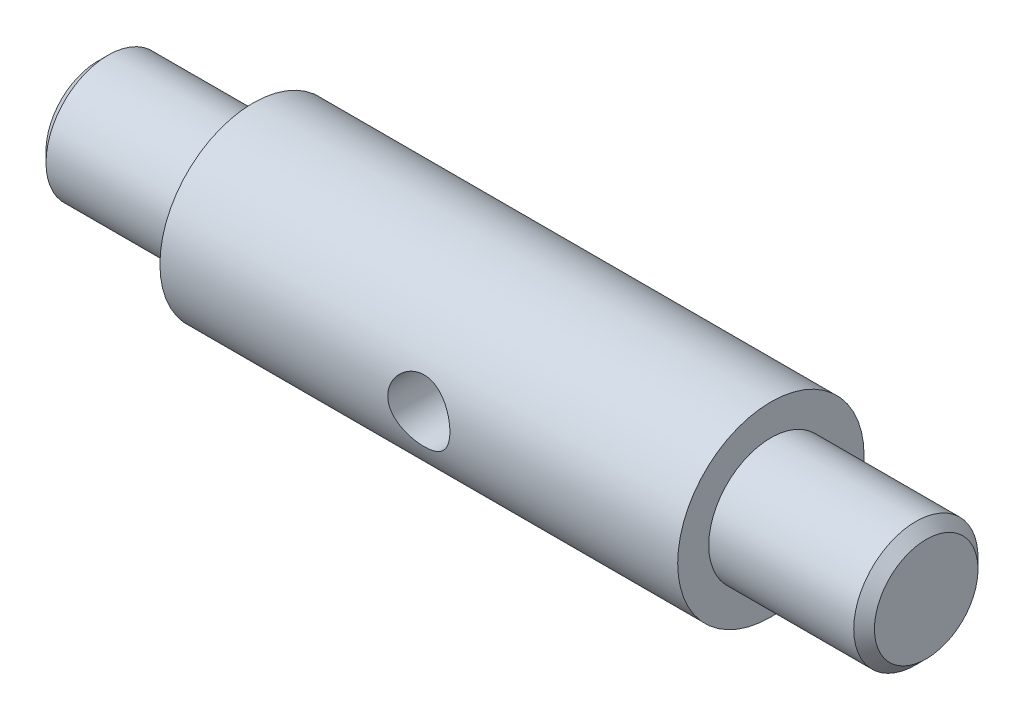
SolidWorks part; units mm, degrees
ref_plane "Front Plane" through (0, 0, 0) normal (0, 0, 1) x (1, 0, 0)
ref_plane "Top Plane" through (0, 0, 0) normal (0, 1, 0) x (1, 0, 0)
ref_plane "Right Plane" through (0, 0, 0) normal (1, 0, 0) x (0, 0, -1)
sketch "Sketch1" plane through (0, 0, 0) normal (0, 0, 1) x (1, 0, 0)
  line L0 (-32, 0) -> (48, 0)
  line L1 (48, 0) -> (48, 6)
  line L2 (48, 6) -> (33, 6)
  line L3 (33, 6) -> (33, 9)
  line L4 (33, 9) -> (-17, 9)
  line L5 (-17, 9) -> (-17, 6)
  line L6 (-17, 6) -> (-32, 6)
  line L7 (-32, 6) -> (-32, 0)
  dimension "D1" = 15
  dimension "D2" = 15
  dimension "D3" = 9
  dimension "D4" = 50
  dimension "D5" = 80
  dimension "D6" = 6
  dimension "D7" = 6
  dimension "D8" = 9
revolve "Revolve5" add sketch "Sketch1" angle 360 about L0
sketch "Sketch2" plane through (0, 0, 0) normal (0, 0, 1) x (1, 0, 0)
  line L0 (-17, 6) -> (-17, -6) construction
  circle A0 centre (8, 0) radius 3
  point P0 (8, 0)
  dimension "D2" = 6
  dimension "D1" = 25
extrude "Cut-Extrude3" cut sketch "Sketch2" against normal through all both and the other way through all
chamfer "Chamfer1" distance 1 angle 45 2 edges at (48, 0, 6) (-32, 0, 6)
hole_wizard "Ø6.0 (6) Diameter Hole1" positions "Sketch3" profile "Sketch4" hole size "Ø6.0" standard "ISO"
sketch "Sketch3" plane through (-32, 0, 0) normal (-1, 0, 0) x (0, 0, 1)
  point P0 (0, 0)
sketch "Sketch4" plane through (-32, 0, 0) normal (0, 1, 0) x (0, 0, 1)
  line L0 (0, 0) -> (0, 46.8026)
  line L1 (0, 46.8026) -> (3, 45)
  line L2 (3, 45) -> (3, 0)
  line L5 (3, 0) -> (0, 0)
  line L10 (0, 46.8026) -> (-3, 45) construction
  line L11 (0, -6.35) -> (0, 107.95) construction
  dimension "Hole Dia." = 6
  dimension "Hole Depth" = 45
  dimension "Drill Angle" = 118
